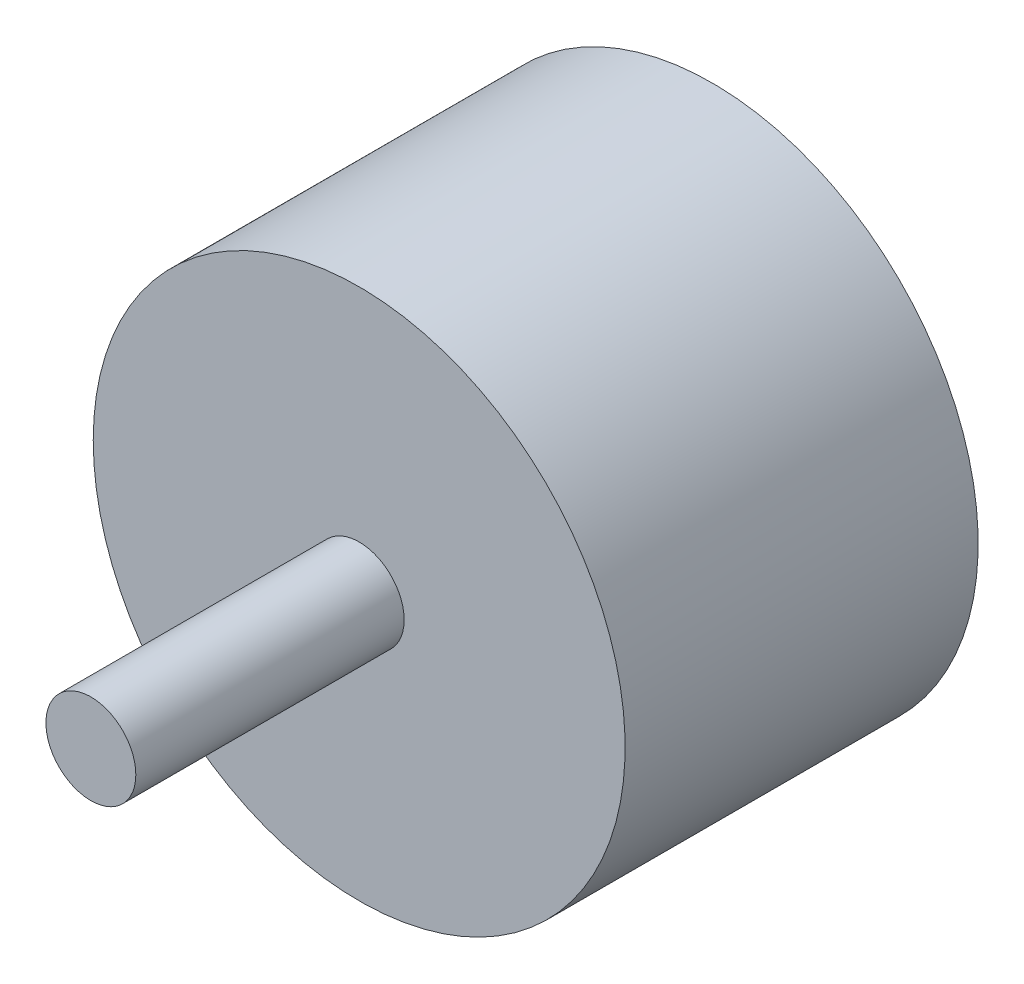
SolidWorks part; units mm, degrees
ref_plane "Front Plane" through (0, 0, 0) normal (0, 0, 1) x (1, 0, 0)
ref_plane "Top Plane" through (0, 0, 0) normal (0, 1, 0) x (1, 0, 0)
ref_plane "Right Plane" through (0, 0, 0) normal (1, 0, 0) x (0, 0, -1)
sketch "Sketch1" plane through (0, 0, 0) normal (0, 0, 1) x (1, 0, 0)
  circle A0 centre (0, 0) radius 14.351
  dimension "D1" = 28.702
extrude "Boss-Extrude1" add sketch "Sketch1" along normal blind 19.05
sketch "Sketch2" plane through (0, 0, 19.05) normal (0, 0, 1) x (1, 0, 0)
  circle A0 centre (0, 0) radius 2.4257
  dimension "D1" = 4.8514
extrude "Boss-Extrude2" add sketch "Sketch2" along normal blind 14.478
sketch "Sketch3" plane through (0, 0, 0) normal (0, 0, -1) x (-1, 0, 0)
  line L0 (0, 0) -> (0, 8.001) construction
  line L1 (0, 0) -> (9.525, 0) construction
  line L2 (0, 0) -> (-9.525, 0) construction
  line L3 (0, 0) -> (0, -8.001) construction
  circle A0 centre (0, 8.001) radius 1.2065
  circle A1 centre (9.525, 0) radius 1.2065
  circle A2 centre (0, -8.001) radius 1.2065
  circle A3 centre (-9.525, 0) radius 1.2065
  dimension "D2" = 2.413
  dimension "D1" = 16.002
  dimension "D3" = 19.05
extrude "Cut-Extrude1" cut sketch "Sketch3" against normal blind 5.08
